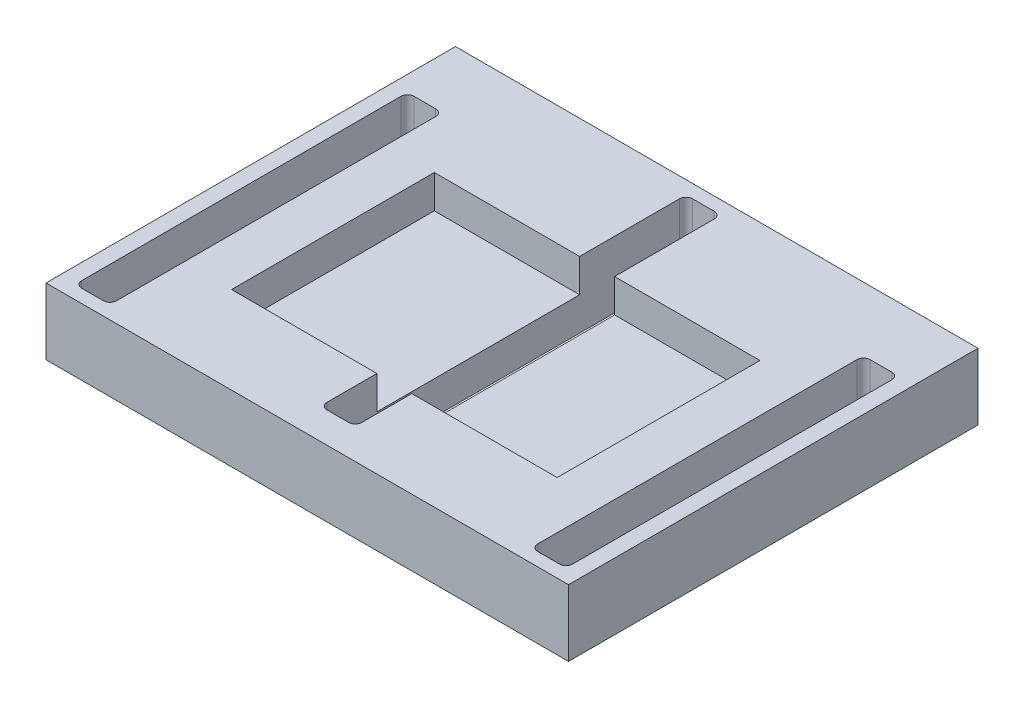
SolidWorks part; units mm, degrees
other "Markup1"
sketch "Sketch5" plane through (73.6, 10, -57.0972) normal (0.5319, 0.8358, -0.1359) x (0.7916, -0.5478, -0.2709)
ref_plane "Front Plane" through (0, 0, 0) normal (0, 0, 1) x (1, 0, 0)
ref_plane "Top Plane" through (0, 0, 0) normal (0, 1, 0) x (1, 0, 0)
ref_plane "Right Plane" through (0, 0, 0) normal (1, 0, 0) x (0, 0, -1)
sketch "00" plane through (0, 0, 0) normal (0, 1, 0) x (1, 0, 0)
  line L0 (0, 0) -> (0, 35)
  line L1 (0, 35) -> (10, 35)
  line L2 (10, 35) -> (21.8, 18.8519)
  line L3 (21.8, 18.8519) -> (46.8, 18.8519)
  line L4 (46.8, 18.8519) -> (58.6, 35)
  line L5 (58.6, 35) -> (68.6, 35)
  line L6 (68.6, 35) -> (68.6, 0)
  line L9 (21.8, 18.8519) -> (34.3, 10.0993) construction
  line L10 (34.3, 10.0993) -> (46.8, 18.8519) construction
  line L11 (34.3, 10.0993) -> (34.3, 2.5993)
  line L12 (34.3, 2.5993) -> (34.3, 42.5993)
  dimension "D1" = 68.6
  dimension "D4" = 25
  dimension "D5" = 20
  dimension "D6" = 10
  dimension "D7" = 35
  dimension "D9" = 0
  dimension "D10" = 0
  dimension "D2" = 0
  dimension "D3" = 35
  dimension "D8" = 7.5
  dimension "D11" = 40
  dimension "D12" = 34.3
sketch "10" plane through (0, 0, 0) normal (0, 1, 0) x (1, 0, 0)
  line L0 (0, 10) -> (0, 45)
  line L1 (0, 45) -> (10, 45)
  line L2 (10, 45) -> (15.8095, 25.8623)
  line L3 (15.8095, 25.8623) -> (40.8095, 25.8623)
  line L4 (40.8095, 25.8623) -> (58.6, 35)
  line L5 (58.6, 35) -> (68.6, 35)
  line L6 (68.6, 35) -> (68.6, 0)
  line L7 (15.8095, 25.8623) -> (28.3095, 17.1097) construction
  line L9 (28.3095, 17.1097) -> (40.8095, 25.8623) construction
  line L10 (28.3095, 17.1097) -> (34.3, 12.5972)
  line L11 (34.3, 12.5972) -> (34.3, 52.5972)
  dimension "D9" = 0
  dimension "D12" = 34.3
  dimension "D1" = 35
  dimension "D2" = 20
  dimension "D3" = 10
  dimension "D6" = 25
  dimension "D7" = 68.6
  dimension "D10" = 10
  dimension "D11" = 0
  dimension "D4" = 35
  dimension "D5" = 7.5
  dimension "D8" = 40
sketch "01" plane through (0, 0, 0) normal (0, 1, 0) x (1, 0, 0)
  line L0 (0, 0) -> (0, 35)
  line L1 (0, 35) -> (10, 35)
  line L2 (10, 35) -> (27.7905, 25.8623)
  line L3 (27.7905, 25.8623) -> (52.7905, 25.8623)
  line L4 (52.7905, 25.8623) -> (58.6, 45)
  line L5 (58.6, 45) -> (68.6, 45)
  line L6 (68.6, 45) -> (68.6, 10)
  line L7 (27.7905, 25.8623) -> (40.2905, 17.1097) construction
  line L8 (40.2905, 17.1097) -> (52.7905, 25.8623) construction
  line L9 (40.2905, 17.1097) -> (34.3, 12.5972)
  line L10 (34.3, 12.5972) -> (34.3, 52.5972)
  dimension "D10" = 0
  dimension "D12" = 34.3
  dimension "D1" = 35
  dimension "D6" = 25
  dimension "D7" = 68.6
  dimension "D11" = 0
  dimension "D4" = 20
  dimension "D5" = 10
  dimension "D9" = 10
  dimension "D2" = 40
  dimension "D3" = 7.5
  dimension "D8" = 35
sketch "11" plane through (0, 0, 0) normal (0, 1, 0) x (1, 0, 0)
  line L0 (0, 10) -> (0, 45)
  line L1 (0, 45) -> (10, 45)
  line L2 (10, 45) -> (21.8, 28.8519)
  line L3 (21.8, 28.8519) -> (46.8, 28.8519)
  line L4 (46.8, 28.8519) -> (58.6, 45)
  line L5 (58.6, 45) -> (68.6, 45)
  line L6 (68.6, 45) -> (68.6, 10)
  line L7 (21.8, 28.8519) -> (34.3, 20.0993) construction
  line L8 (34.3, 20.0993) -> (46.8, 28.8519) construction
  line L9 (34.3, 20.0993) -> (34.3, 12.5993)
  line L10 (34.3, 12.5993) -> (34.3, 52.5993)
  dimension "D4" = 25
  dimension "D9" = 0
  dimension "D12" = 34.3
  dimension "D1" = 35
  dimension "D7" = 68.6
  dimension "D10" = 10
  dimension "D8" = 40
  dimension "D2" = 10
  dimension "D3" = 20
  dimension "D11" = 10
  dimension "D5" = 35
  dimension "D6" = 7.5
sketch "Sketch1" plane through (0, 0, 0) normal (0, 1, 0) x (1, 0, 0)
  line L0 (34.3, 12.5972) -> (34.3, 52.5972) construction
  line L1 (-5, 57.0972) -> (34.3, 57.0972)
  line L2 (-5, 57.0972) -> (-5, -4.5)
  line L3 (-5, -4.5) -> (34.3, -4.5)
  line L4 (34.3, 57.0972) -> (34.3, 55.0972)
  line L5 (-2.625, 45) -> (-2.625, 0)
  line L6 (2.625, 0) -> (2.625, 45)
  line L7 (0, 47.5) -> (-2.625, 47.5)
  line L8 (-2.625, 47.5) -> (-2.625, 45)
  line L9 (0, 47.5) -> (2.625, 47.5)
  line L10 (2.625, 47.5) -> (2.625, 45)
  line L11 (0, -2.5) -> (-2.625, -2.5)
  line L12 (-2.625, -2.5) -> (-2.625, 0)
  line L13 (0, -2.5) -> (2.625, -2.5)
  line L14 (2.625, -2.5) -> (2.625, 0)
  line L15 (31.675, 2.5993) -> (31.675, 52.5972)
  line L16 (34.3, 55.0972) -> (31.675, 55.0972)
  line L17 (31.675, 55.0972) -> (31.675, 52.5972)
  line L18 (34.3, 0.0993) -> (31.675, 0.0993)
  line L19 (31.675, 0.0993) -> (31.675, 2.5993)
  line L21 (34.3, 0.0993) -> (34.3, -4.5)
  circle A0 centre (0, 0) radius 2.625 construction
  circle A1 centre (0, 0) radius 2.5 construction
  circle A2 centre (0, 45) radius 2.625 construction
  circle A3 centre (0, 45) radius 2.5 construction
  circle A4 centre (34.3, 52.5972) radius 2.625 construction
  circle A5 centre (34.3, 52.5972) radius 2.5 construction
  circle A6 centre (34.3, 2.5993) radius 2.625 construction
  circle A7 centre (34.3, 2.5993) radius 2.5 construction
  point P38 (-1.3125, -2.5)
  dimension "D2" = 5.25
  dimension "D3" = 5
  dimension "D4" = 34.3
  dimension "D1" = 5
  dimension "D5" = 2
  dimension "D6" = 2
extrude "Boss-Extrude1" add sketch "Sketch1" along normal blind 10
fillet "Fillet1" radius 1 6 edges at (31.675, 5, -0.0993) (31.675, 5, -55.0972) (2.625, 5, 2.5) (-2.625, 5, 2.5) (2.625, 5, -47.5) (-2.625, 5, -47.5)
sketch "Sketch2" plane through (0, 10, 0) normal (0, 1, 0) x (1, 0, 0)
  line L0 (31.675, 1.0993) -> (31.675, 54.0972) construction
  line L1 (31.675, 39.1019) -> (9.8095, 39.1019)
  line L2 (31.675, 39.1019) -> (31.675, 8.6019)
  line L3 (31.675, 8.6019) -> (9.8095, 8.6019)
  line L4 (9.8095, 39.1019) -> (9.8095, 8.6019)
  dimension "D1" = 6
  dimension "D2" = 10.25
  dimension "D3" = 10.25
extrude "Cut-Extrude1" cut sketch "Sketch2" against normal blind 5
mirror "Mirror1" about plane through (34.3, 10, -0.0993) normal (-1, 0, 0) of "Fillet1", "Boss-Extrude1", "Cut-Extrude1"
sketch "Sketch4" plane through (0, 10, 0) normal (0, 1, 0) x (1, 0, 0)
  line L0 (9.8095, 39.1019) -> (9.8095, 8.6019) construction
  line L1 (9.9095, 28.8519) -> (34.3, 28.8519)
  line L2 (9.9095, 28.8519) -> (9.9095, 8.8519)
  line L3 (9.9095, 8.8519) -> (34.3, 8.8519)
  line L4 (34.3, 28.8519) -> (34.3, 21.4769)
  line L5 (21.8, 18.8519) -> (14.9095, 18.8519) construction
  line L6 (14.9095, 21.4769) -> (34.3, 21.4769)
  line L7 (14.9095, 16.2269) -> (34.3, 16.2269)
  line L8 (34.3, 2.5993) -> (34.3, 42.5993) construction
  line L9 (34.3, 16.2269) -> (34.3, 8.8519)
  circle A0 centre (14.9095, 18.8519) radius 2.625 construction
  arc A1 (14.9095, 21.4769) -> (14.9095, 16.2269) centre (14.9095, 18.8519) ccw
  dimension "D3" = 5.25
  dimension "D1" = 0.1
  dimension "D2" = 20
  dimension "D4" = 10
  dimension "D5" = 5
  dimension "D6" = 0
extrude "Boss-Extrude2" [suppressed] add sketch "Sketch4" against normal blind 4.9 separate body
mirror "Mirror3" [suppressed]
equation "\"D12@00\"=\"D1@00\"/2"
equation "\"D12@10\"=\"D7@10\"/2"
equation "\"D12@01\"=\"D7@01\"/2"
equation "\"D12@11\"=\"D7@11\"/2"
equation "\"D4@Sketch4\"=\"D2@Sketch4\"/2"
